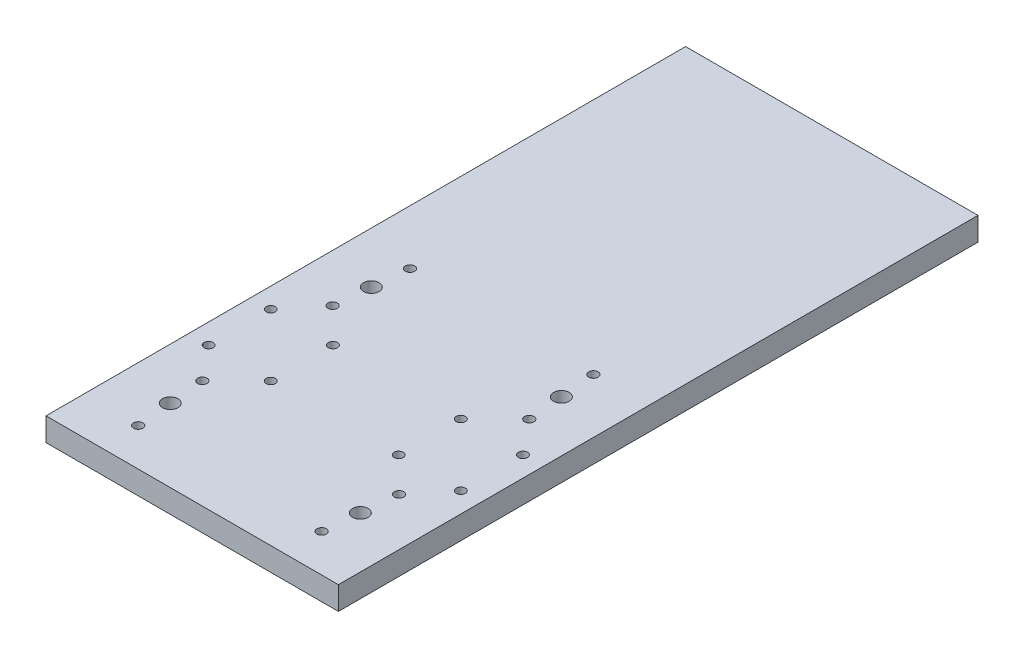
SolidWorks part; units mm, degrees
ref_plane "Alzado" through (0, 0, 0) normal (0, 0, 1) x (1, 0, 0)
ref_plane "Planta" through (0, 0, 0) normal (0, 1, 0) x (1, 0, 0)
ref_plane "Vista lateral" through (0, 0, 0) normal (1, 0, 0) x (0, 0, -1)
sketch "Croquis1" plane through (0, 0, 0) normal (0, 1, 0) x (1, 0, 0)
  line L0 (-8.6194, -80) -> (-50008.6194, -80) construction
  line L1 (80, -175) -> (-80, -175)
  line L2 (80, -175) -> (80, 175)
  line L3 (80, 175) -> (-80, 175)
  line L4 (-80, -175) -> (-80, 175)
  line L5 (80, -175) -> (-80, 175) construction
  line L6 (80, 175) -> (-80, -175) construction
  line L7 (0, 0) -> (0, -50000) construction
  circle A0 centre (52, -135) radius 4.25
  circle A1 centre (52, -135) radius 6 construction
  circle A2 centre (52, -25) radius 4.25
  circle A3 centre (-52, -135) radius 4.25
  circle A4 centre (-52, -25) radius 4.25
  point P0 (0, 0)
  dimension "D3" = 8.5
  dimension "D1" = 160
  dimension "D2" = 350
extrude "Saliente-Extruir1" add sketch "Croquis1" along normal mid plane 12.7
hole_wizard "Taladro roscado 1/4-201" positions "Croquis2" profile "Croquis3" tap size "1/4-20" standard "Ansi Inch" end condition through all
sketch "Croquis2" plane through (0, 6.35, 0) normal (0, 1, 0) x (1, 0, 0)
  line L0 (199991.3806, -80) -> (-250008.6194, -80) construction
  line L1 (199991.3806, -80) -> (-250008.6194, -80) construction
  line L2 (0, 200000) -> (0, -250000) construction
  line L3 (0, 200000) -> (0, -250000) construction
  point P0 (50.1806, -154.3647)
  point P3 (53.8194, -115.6353)
  point P10 (50.1806, -5.6353)
  point P11 (53.8194, -44.3647)
  point P14 (-53.8194, -44.3647)
  point P15 (-50.1806, -5.6353)
  point P16 (-53.8194, -115.6353)
  point P17 (-50.1806, -154.3647)
sketch "Croquis3" plane through (50.1806, 6.35, 154.3647) normal (1, 0, 0) x (0, 0, 1)
  line L0 (0, 0) -> (0, 12.7)
  line L1 (0, 12.7) -> (2.5527, 12.7)
  line L2 (2.5527, 12.7) -> (2.5527, 0)
  line L5 (2.5527, 0) -> (0, 0)
  line L11 (0, -6.35) -> (0, 107.95) construction
  dimension "Diámetro de perforador para roscar hasta el siguiente" = 5.1054
  dimension "Profundidad de perforador para roscar hasta el siguiente" = 12.7
cosmetic thread "Hole Thread4" parameters "D1"=12.7, "D2"=6.35
cosmetic thread "Hole Thread5" parameters "D1"=12.7, "D2"=6.35
cosmetic thread "Hole Thread17" parameters "D1"=12.7, "D2"=6.35
cosmetic thread "Hole Thread18" parameters "D1"=12.7, "D2"=6.35
cosmetic thread "Hole Thread23" parameters "D1"=12.7, "D2"=6.35
cosmetic thread "Hole Thread24" parameters "D1"=12.7, "D2"=6.35
cosmetic thread "Hole Thread25" parameters "D1"=12.7, "D2"=6.35
cosmetic thread "Hole Thread26" parameters "D1"=12.7, "D2"=6.35
hole_wizard "Taladro roscado M6x1.01" positions "Croquis4" profile "Croquis5" tap size "M6x1.0" standard "Ansi Metric" end condition through all
sketch "Croquis4" plane through (0, 6.35, 0) normal (0, 1, 0) x (1, 0, 0)
  line L0 (0, 0) -> (0, -50000) construction
  point P0 (69, -97)
  point P4 (35, -63)
  point P7 (35, -97)
  point P10 (69, -63)
  point P17 (-69, -63)
  point P18 (-35, -97)
  point P19 (-35, -63)
  point P20 (-69, -97)
sketch "Croquis5" plane through (69, 6.35, 97) normal (1, 0, 0) x (0, 0, 1)
  line L0 (0, 0) -> (0, 12.7)
  line L1 (0, 12.7) -> (2.5, 12.7)
  line L2 (2.5, 12.7) -> (2.5, 0)
  line L5 (2.5, 0) -> (0, 0)
  line L11 (0, -6.35) -> (0, 107.95) construction
  dimension "Diámetro de perforador para roscar hasta el siguiente" = 5
  dimension "Profundidad de perforador para roscar hasta el siguiente" = 12.7
cosmetic thread "Hole Thread27" parameters "D1"=12.7, "D2"=6
cosmetic thread "Hole Thread28" parameters "D1"=12.7, "D2"=6
cosmetic thread "Hole Thread29" parameters "D1"=12.7, "D2"=6
cosmetic thread "Hole Thread30" parameters "D1"=12.7, "D2"=6
cosmetic thread "Hole Thread31" parameters "D1"=12.7, "D2"=6
cosmetic thread "Hole Thread32" parameters "D1"=12.7, "D2"=6
cosmetic thread "Hole Thread33" parameters "D1"=12.7, "D2"=6
cosmetic thread "Hole Thread34" parameters "D1"=12.7, "D2"=6
